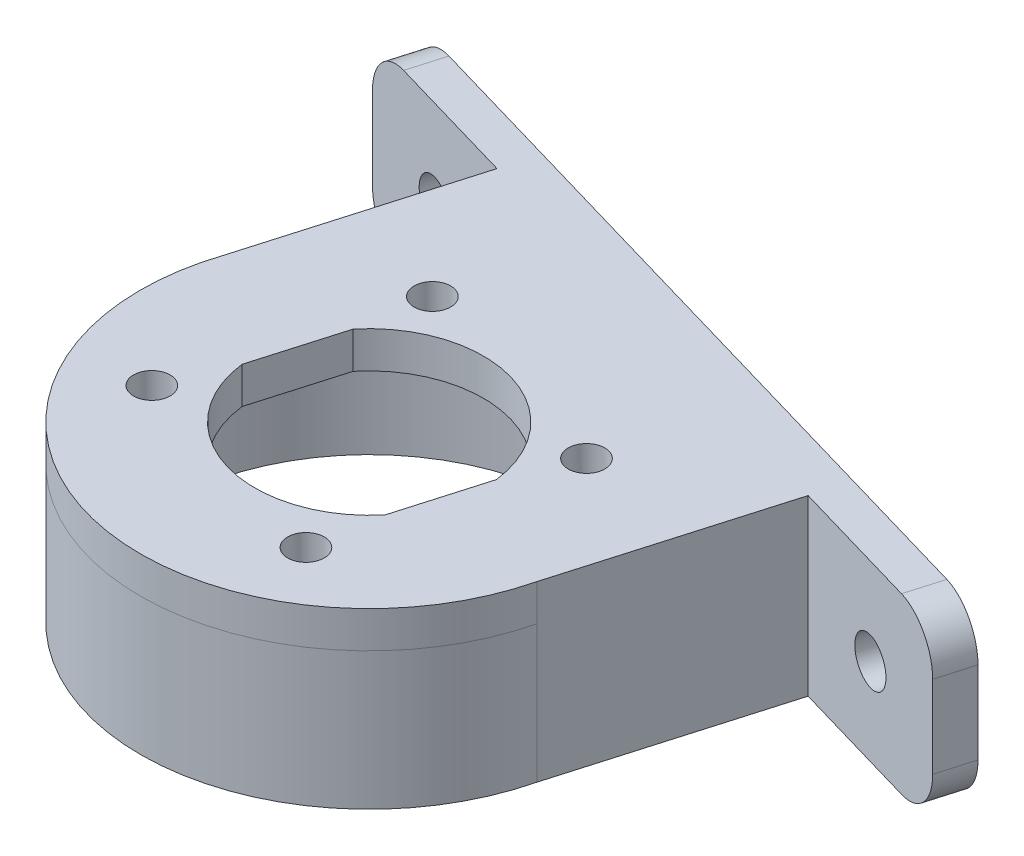
SolidWorks part; units mm, degrees
ref_plane "Front Plane" through (0, 0, 0) normal (0, 0, 1) x (1, 0, 0)
ref_plane "Top Plane" through (0, 0, 0) normal (0, 1, 0) x (1, 0, 0)
ref_plane "Right Plane" through (0, 0, 0) normal (1, 0, 0) x (0, 0, -1)
sketch "Sketch1" plane through (0, 0, 0) normal (0, 1, 0) x (1, 0, 0)
  line L0 (8.8101, -41.586) -> (11.5467, -32.178)
  line L1 (30.8948, -48.0099) -> (33.6314, -38.6018)
  circle A0 centre (29.6465, -55.432) radius 2
  circle A1 centre (36.5588, -31.6681) radius 2
  circle A2 centre (12.7949, -24.7558) radius 2
  circle A3 centre (5.8827, -48.5197) radius 2
  circle A4 centre (21.2207, -40.0939) radius 4
  arc A5 (33.6314, -38.6018) -> (11.5467, -32.178) centre (21.2207, -40.0939) ccw
  circle A6 centre (21.2207, -40.0939) radius 25
  arc A7 (8.8101, -41.586) -> (30.8948, -48.0099) centre (21.2207, -40.0939) ccw
  dimension "D1" = 50
extrude "Boss-Extrude1" add sketch "Sketch1" along normal blind 4 contours A6 A7 L0 A5 L1 A0 A1 A2 A3
sketch "Sketch2" plane through (0, 0, 0) normal (0, -1, 0) x (1, 0, 0)
  circle A0 centre (21.2207, 40.0939) radius 25
  circle A1 centre (21.2207, 40.0939) radius 22.5
  dimension "D2" = 45
  dimension "D1" = 50
extrude "Boss-Extrude2" add sketch "Sketch2" along normal blind 15
ref_plane "Plane1" through (-2.1147, 0, 7.2701) normal (0.2793, 0, -0.9602) x (-0.9602, 0, -0.2793)
sketch "Sketch4" plane through (-2.1147, 0, 7.2701) normal (0.2793, 0, -0.9602) x (-0.9602, 0, -0.2793)
  line L0 (-56.5744, -15) -> (-6.5744, -15) construction
  line L1 (-56.5512, -15) -> (-6.5958, -15)
  line L2 (-56.5512, -15) -> (-56.5512, 4)
  line L3 (-56.5512, 4) -> (-6.5958, 4)
  line L4 (-6.5958, -15) -> (-6.5958, 4)
  line L5 (-6.5744, 4) -> (-56.5744, 4) construction
extrude "Boss-Extrude7" add sketch "Sketch4" against normal up to next
sketch "Sketch5" plane through (-2.1147, 0, 7.2701) normal (0.2793, 0, -0.9602) x (-0.9602, 0, -0.2793)
  line L0 (-56.5512, -5.5) -> (19.3148, -5.5) construction
  line L1 (-56.5512, 4) -> (-56.5512, -15) construction
  line L5 (-76.5512, 4) -> (-76.5512, -15)
  line L6 (-76.5512, 4) -> (-76.5512, -15)
  line L7 (-76.5512, 4) -> (13.4042, 4)
  line L8 (13.4042, -15) -> (13.4042, 4)
  line L9 (13.4042, -15) -> (13.4042, 4)
  line L10 (13.4042, 4) -> (13.3182, 3.7861)
  line L11 (-76.5512, -15) -> (13.4042, -15)
  dimension "D1" = 20
  dimension "D2" = 20
extrude "Boss-Extrude8" add sketch "Sketch5" along normal blind 4
sketch "Sketch7" plane through (-0.9975, 0, 3.4293) normal (0.2793, 0, -0.9602) x (-0.9602, 0, -0.2793)
  line L0 (-76.5512, 4) -> (-76.5512, -15) construction
  line L2 (13.4042, -15) -> (13.4042, 4) construction
  line L3 (-76.5512, -15) -> (13.4042, -15) construction
  circle A0 centre (-66.5512, -5.5) radius 2.5
  circle A1 centre (3.4042, -5.5) radius 2.5
  point P8 (13.4042, -5.5)
  dimension "D1" = 5
  dimension "D3" = 5
  dimension "D2" = 10
  dimension "D4" = 10
  dimension "D5" = 69.9554
  dimension "D6" = 9.5
extrude "Cut-Extrude1" cut sketch "Sketch7" against normal blind 4
fillet "Fillet1" radius 5 1 edges at (71.9487, -15, 26.7303)
fillet "Fillet2" radius 5 3 edges at (-14.4268, 4, 1.6059) (-14.4268, -15, 1.6059) (71.9487, 4, 26.7303)
